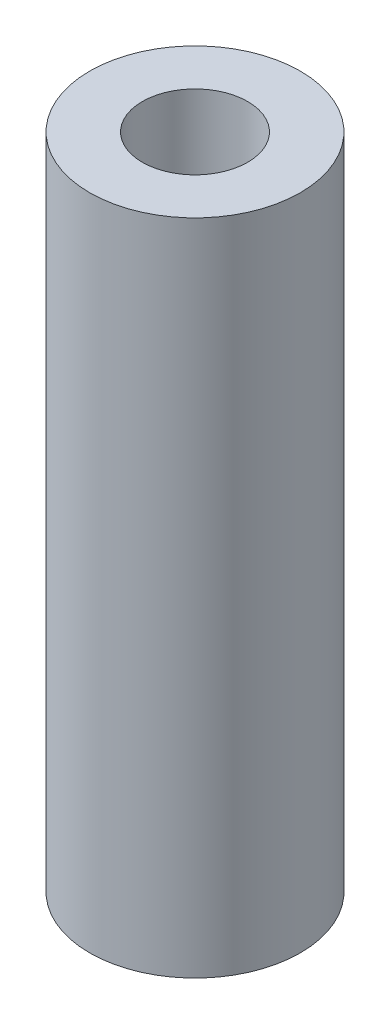
SolidWorks part; units mm, degrees
ref_plane "Plan de face" through (0, 0, 0) normal (0, 0, 1) x (1, 0, 0)
ref_plane "Plan de dessus" through (0, 0, 0) normal (0, 1, 0) x (1, 0, 0)
ref_plane "Plan de droite" through (0, 0, 0) normal (1, 0, 0) x (0, 0, -1)
sketch "Esquisse1" plane through (0, 0, 0) normal (0, 1, 0) x (1, 0, 0)
  circle A0 centre (0, 0) radius 4
  circle A1 centre (0, 0) radius 8
  dimension "D1" = 8
  dimension "D2" = 16
extrude "Boss.-Extru.1" add sketch "Esquisse1" along normal blind 30
sketch "Esquisse3" plane through (0, 0, 0) normal (0, -1, 0) x (1, 0, 0)
  circle A0 centre (0, 0) radius 4
  circle A1 centre (0, 0) radius 8
extrude "Boss.-Extru.2" add sketch "Esquisse3" along normal blind 20
ref_plane "Plan1" through (0, 0, 8) normal (0, 0, 1) x (1, 0, 0)
